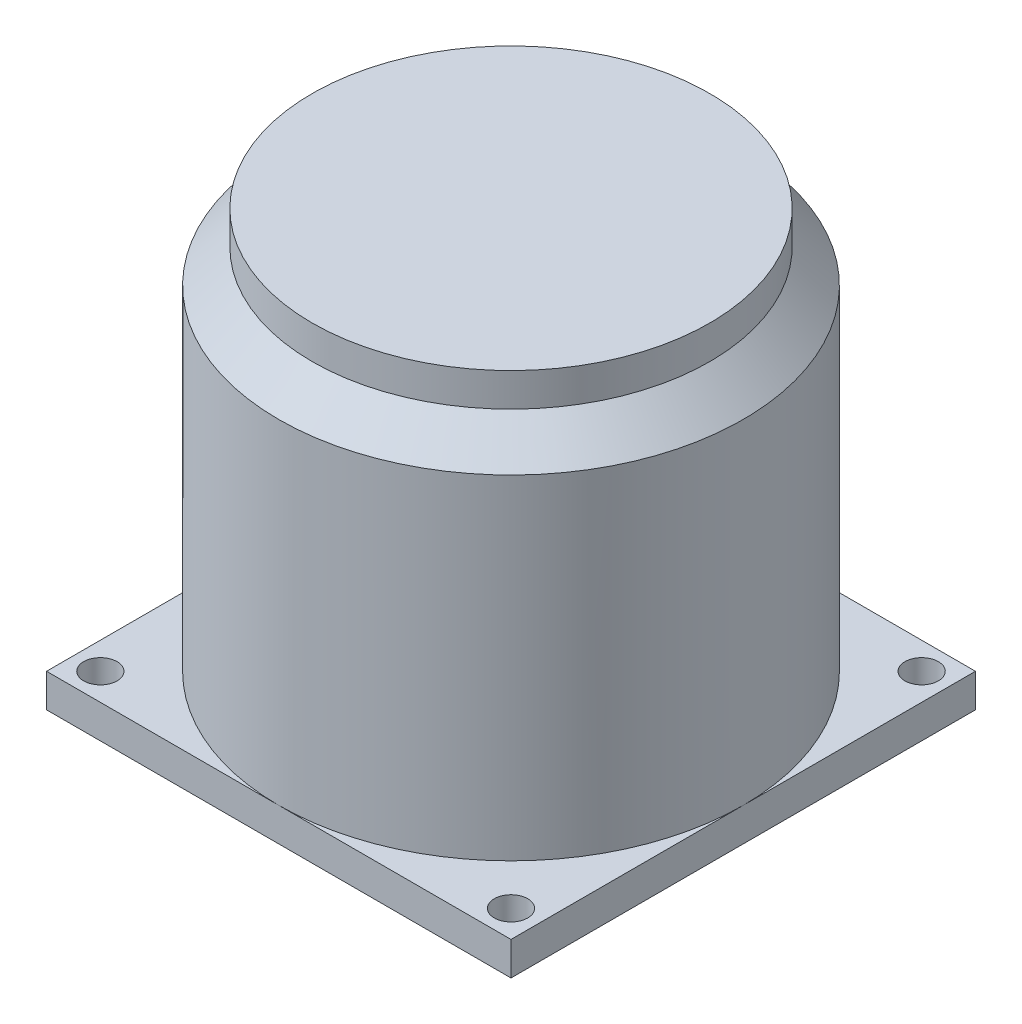
SolidWorks part; units mm, degrees
ref_plane "Front Plane" through (0, 0, 0) normal (0, 0, 1) x (1, 0, 0)
ref_plane "Top Plane" through (0, 0, 0) normal (0, 1, 0) x (1, 0, 0)
ref_plane "Right Plane" through (0, 0, 0) normal (1, 0, 0) x (0, 0, -1)
sketch "Sketch1" plane through (0, 0, 0) normal (0, 1, 0) x (1, 0, 0)
  line L1 (139, -139) -> (-139, -139)
  line L2 (139, -139) -> (139, 139)
  line L3 (139, 139) -> (-139, 139)
  line L4 (-139, -139) -> (-139, 139)
  line L5 (139, -139) -> (-139, 139) construction
  line L6 (139, 139) -> (-139, -139) construction
  circle A0 centre (0, 0) radius 139
  point P0 (0, 0)
  dimension "D3" = 278
  dimension "D1" = 278
  dimension "D2" = 278
extrude "Boss-Extrude5" add sketch "Sketch1" along normal blind 220 contours A0 L3
chamfer "Chamfer6" distance 20 1 edges at (0, 220, 139)
sketch "Sketch9" plane through (0, 220, 0) normal (0, 1, 0) x (1, 0, 0)
  circle A0 centre (0, 0) radius 119
  dimension "D1" = 238
extrude "Boss-Extrude6" add sketch "Sketch9" along normal blind 20
sketch "Sketch10" plane through (0, 0, 0) normal (0, -1, 0) x (1, 0, 0)
  line L0 (0, 139) -> (0, -139)
  line L5 (-139, -139) -> (139, -139)
  line L6 (-139, -139) -> (-139, 139)
  line L7 (-139, 139) -> (139, 139)
  line L8 (139, -139) -> (139, 139)
  line L9 (-139, -139) -> (139, 139) construction
  line L10 (-139, 139) -> (139, -139) construction
  line L11 (-139, 0) -> (139, 0)
  circle A0 centre (-122.8993, 122.8993) radius 10
  circle A1 centre (-122.8993, -122.8993) radius 10
  circle A2 centre (122.8993, -122.8993) radius 10
  circle A3 centre (122.8993, 122.8993) radius 10
  point P0 (0, 6.1317)
  point P1 (0, 0)
  circle M11 centre (0, 0) radius 139
  dimension "D1" = 278
  dimension "D2" = 278
extrude "Boss-Extrude7" add sketch "Sketch10" along normal blind 20 contours L7 L6 A0 M11 | L8 L7 A3 M11 | L5 L8 A2 M11 | L6 L5 A1 M11 | L11 L0 M11 | L11 L0 M11 | L0 L11 M11 | L11 L0 M11
